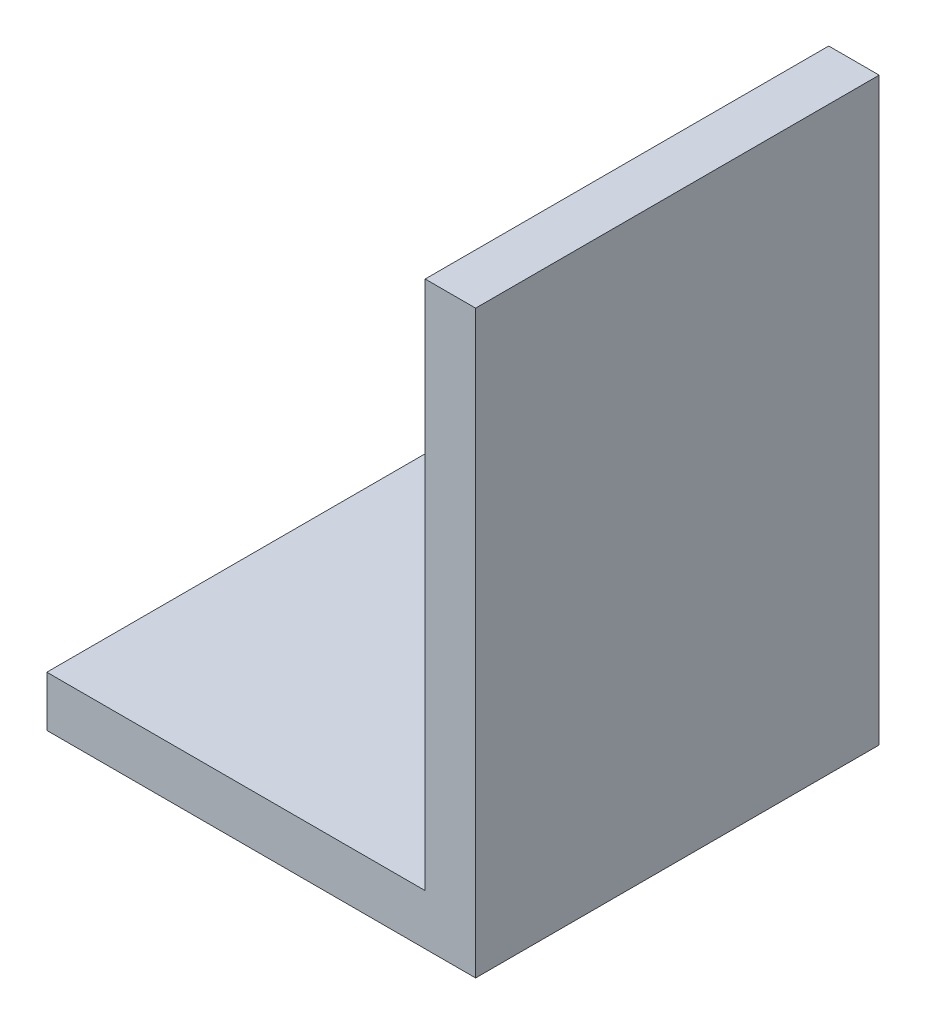
SolidWorks part; units mm, degrees
ref_plane "Front Plane" through (0, 0, 0) normal (0, 0, 1) x (1, 0, 0)
ref_plane "Top Plane" through (0, 0, 0) normal (0, 1, 0) x (1, 0, 0)
ref_plane "Right Plane" through (0, 0, 0) normal (1, 0, 0) x (0, 0, -1)
sketch "Outrigger section profile" plane through (0, 0, 0) normal (0, 0, 1) x (1, 0, 0)
  line L0 (126, 7) -> (143, 7)
  line L1 (143, 7) -> (143, 30)
  line L2 (143, 30) -> (141, 30)
  line L3 (141, 30) -> (141, 9)
  line L4 (141, 9) -> (126, 9)
  line L5 (126, 9) -> (126, 7)
extrude "Outrigger section" add sketch "Outrigger section profile" along normal blind 16
